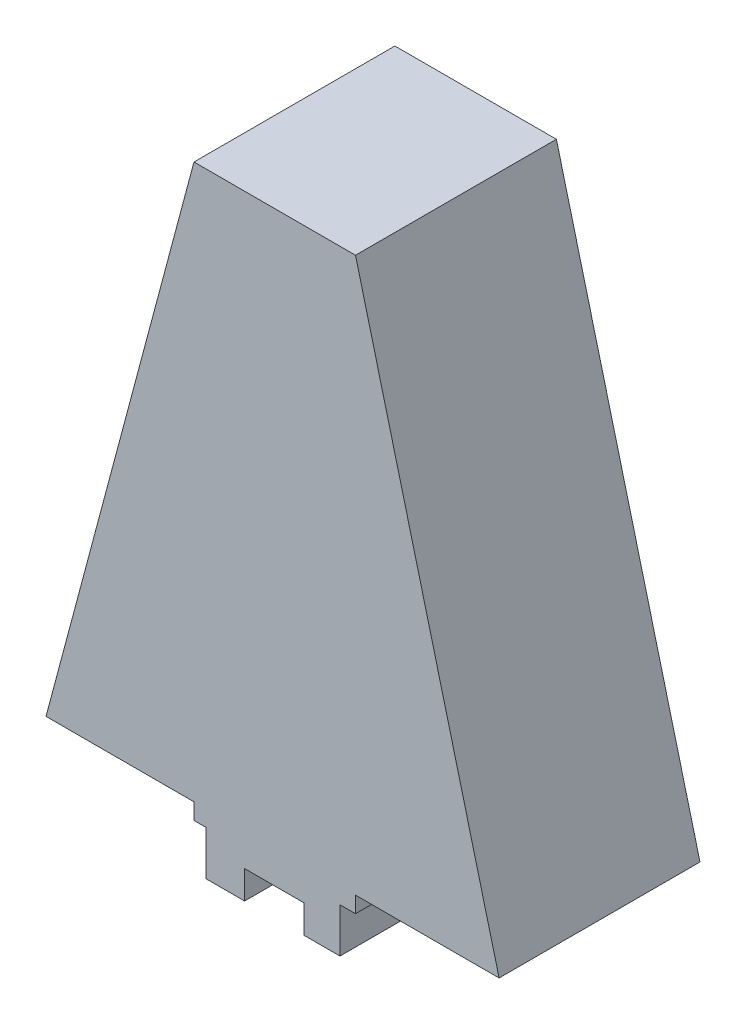
SolidWorks part; units mm, degrees
ref_plane "Front Plane" through (0, 0, 0) normal (0, 0, 1) x (1, 0, 0)
ref_plane "Top Plane" through (0, 0, 0) normal (0, 1, 0) x (1, 0, 0)
ref_plane "Right Plane" through (0, 0, 0) normal (1, 0, 0) x (0, 0, -1)
sketch "Sketch2" plane through (0, 0, 0) normal (0, 0, 1) x (1, 0, 0)
  line L0 (0.0082, -0.071) -> (0.0101, -0.071)
  line L1 (-0.01, 0) -> (0.0101, 0)
  line L2 (-0.01, -0.069) -> (-0.01, -0.071)
  line L3 (-0.01, -0.071) -> (-0.0085, -0.071)
  line L4 (0.0101, -0.069) -> (0.0101, -0.071)
  line L5 (-0.0085, -0.0765) -> (-0.0037, -0.0765)
  line L6 (-0.0085, -0.0765) -> (-0.0085, -0.073)
  line L8 (-0.0037, -0.0765) -> (-0.0037, -0.073)
  line L9 (0.0037, -0.0765) -> (0.0082, -0.0765)
  line L10 (0.0037, -0.0765) -> (0.0037, -0.073)
  line L12 (0.0082, -0.0765) -> (0.0082, -0.073)
  line L13 (-0.0037, -0.073) -> (0.0037, -0.073)
  line L14 (-0.0085, -0.073) -> (-0.0085, -0.071)
  line L16 (0.0082, -0.073) -> (0.0082, -0.071)
  line L17 (-0.01, -0.069) -> (-0.0284, -0.069)
  line L18 (-0.0284, -0.069) -> (-0.01, 0)
  line L19 (0.0101, -0.069) -> (0.028, -0.069)
  line L20 (0.028, -0.069) -> (0.0101, 0)
  point P4 (0, 0)
  point P22 (0, 0)
  point P23 (0, 0)
  point P24 (0, 0)
  point P25 (0, 0)
  point P26 (0, 0)
  point P27 (0, 0)
  point P28 (0, 0)
extrude "Boss-Extrude1" add sketch "Sketch2" along normal blind 0.025
